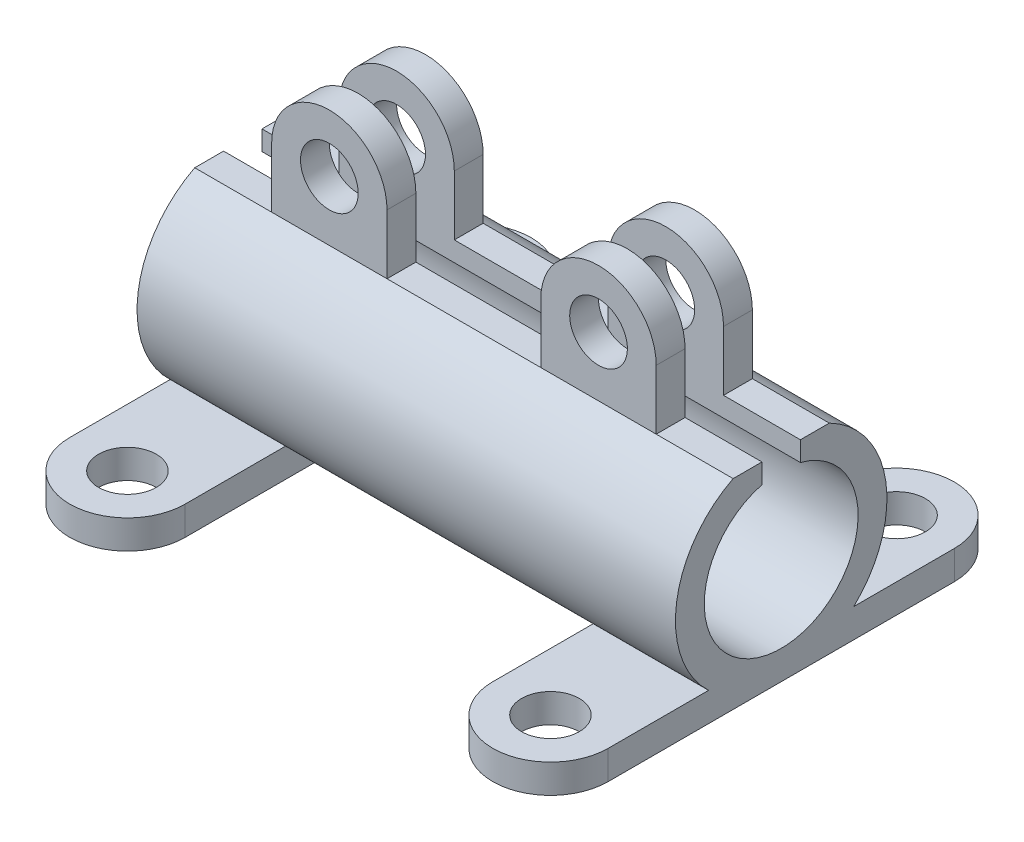
SolidWorks part; units mm, degrees
ref_plane "Front Plane" through (0, 0, 0) normal (0, 0, 1) x (1, 0, 0)
ref_plane "Top Plane" through (0, 0, 0) normal (0, 1, 0) x (1, 0, 0)
ref_plane "Right Plane" through (0, 0, 0) normal (1, 0, 0) x (0, 0, -1)
sketch "Sketch2" plane through (0, 0, 0) normal (0, 1, 0) x (1, 0, 0)
  line L0 (-110, -90) -> (-110, 90) construction
  line L1 (-140, -90) -> (-140, 90)
  line L2 (-80, -90) -> (-80, 90)
  line L3 (0, 0) -> (0, 151.295) construction
  line L4 (-110, 0) -> (0, 0) construction
  line L5 (110, -90) -> (110, 90) construction
  line L6 (140, -90) -> (140, 90)
  line L7 (80, -90) -> (80, 90)
  arc A0 (-140, -90) -> (-80, -90) centre (-110, -90) ccw
  arc A1 (-80, 90) -> (-140, 90) centre (-110, 90) ccw
  circle A2 centre (-110, 90) radius 15
  circle A3 centre (-110, -90) radius 15
  circle A4 centre (110, -90) radius 15
  circle A5 centre (110, 90) radius 15
  arc A6 (140, -90) -> (80, -90) centre (110, -90) cw
  arc A7 (80, 90) -> (140, 90) centre (110, 90) cw
  point P2 (-110, 0)
  point P19 (110, 0)
  dimension "D2" = 30
  dimension "D4" = 30
  dimension "D1" = 180
  dimension "D3" = 280
extrude "Boss-Extrude1" add sketch "Sketch2" along normal blind 15
sketch "Sketch3" plane through (0, 0, 0) normal (1, 0, 0) x (0, 0, -1)
  line L0 (90, 0) -> (-90, 0) construction
  line L1 (90, 15) -> (-90, 15) construction
  line L2 (-10, 165) -> (-10, 93.7298)
  line L11 (25, 103.9898) -> (25, 165)
  line L12 (25, 165) -> (10, 165)
  line L14 (-25, 165) -> (-10, 165)
  line L15 (10, 165) -> (10, 93.7298)
  line L16 (0, 55) -> (0, 165) construction
  line L17 (-25, 103.9898) -> (-25, 165)
  arc A0 (-25, 103.9898) -> (25, 103.9898) centre (0, 55) ccw
  arc A1 (-10, 93.7298) -> (10, 93.7298) centre (0, 55) ccw
  point P4 (0, 165)
  point P6 (0, 0)
  point P18 (0, 0)
  dimension "D1" = 110
  dimension "D2" = 55
  dimension "D3" = 10
  dimension "D5" = 50
  dimension "D6" = 165
extrude "Boss-Extrude2" add sketch "Sketch3" along normal mid plane 280
sketch "Sketch4" plane through (0, 0, 25) normal (0, 0, 1) x (1, 0, 0)
  line L0 (-140, 103.9898) -> (-100, 103.9898)
  line L1 (140, 103.9898) -> (-140, 103.9898) construction
  line L2 (-100, 103.9898) -> (-100, 135)
  line L3 (140, 165) -> (-140, 165) construction
  line L5 (-40, 135) -> (-40, 103.9898)
  line L11 (0, 0) -> (0, 165) construction
  line L12 (-80, 0) -> (80, 0) construction
  line L18 (-140, 103.9898) -> (-140, 165)
  line L23 (-140, 165) -> (-70, 165)
  line L24 (-70, 165) -> (70, 165)
  line L25 (0, 165) -> (0, 103.9898)
  line L26 (40, 103.9898) -> (-40, 103.9898)
  line L27 (140, 165) -> (70, 165)
  line L28 (140, 103.9898) -> (140, 165)
  line L29 (40, 135) -> (40, 103.9898)
  line L30 (100, 103.9898) -> (100, 135)
  line L31 (140, 103.9898) -> (100, 103.9898)
  arc A0 (-40, 135) -> (-100, 135) centre (-70, 135) ccw
  circle A1 centre (-70, 135) radius 15
  circle A4 centre (70, 135) radius 15
  arc A5 (40, 135) -> (100, 135) centre (70, 135) cw
  line M6 (-140, 165) -> (-140, 103.9898)
  line M7 (-140, 103.9898) -> (140, 103.9898)
  line M8 (140, 103.9898) -> (140, 165)
  line M9 (140, 165) -> (-140, 165)
  dimension "D1" = 30
  dimension "D2" = 70
  dimension "D3" = 30
extrude "Cut-Extrude2" cut sketch "Sketch4" against normal through all and the other way through all contours A0 L2 M9 M6 M7 | A1 | A0 L5 L25 L24 M7 | L29 A5 L25 M9 M7 | A4 | A5 L30 M9 M7 M8
